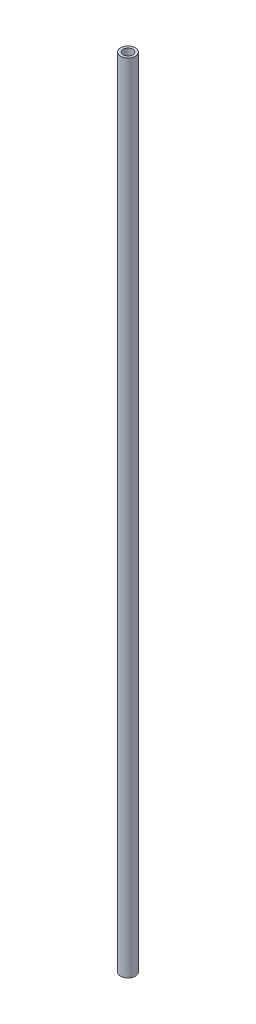
SolidWorks part; units mm, degrees
material "Hexcel AS4C (3000 丝)"
ref_plane "Front Plane" through (0, 0, 0) normal (0, 0, 1) x (1, 0, 0)
ref_plane "Top Plane" through (0, 0, 0) normal (0, 1, 0) x (1, 0, 0)
ref_plane "Right Plane" through (0, 0, 0) normal (1, 0, 0) x (0, 0, -1)
sketch "Sketch1" plane through (0, 0, 0) normal (0, 1, 0) x (1, 0, 0)
  circle A0 centre (0, 0) radius 2.9
  circle A1 centre (0, 0) radius 1.9
  dimension "D1" = 5.8
  dimension "D2" = 1
extrude "Boss-Extrude1" add sketch "Sketch1" along normal blind 313
